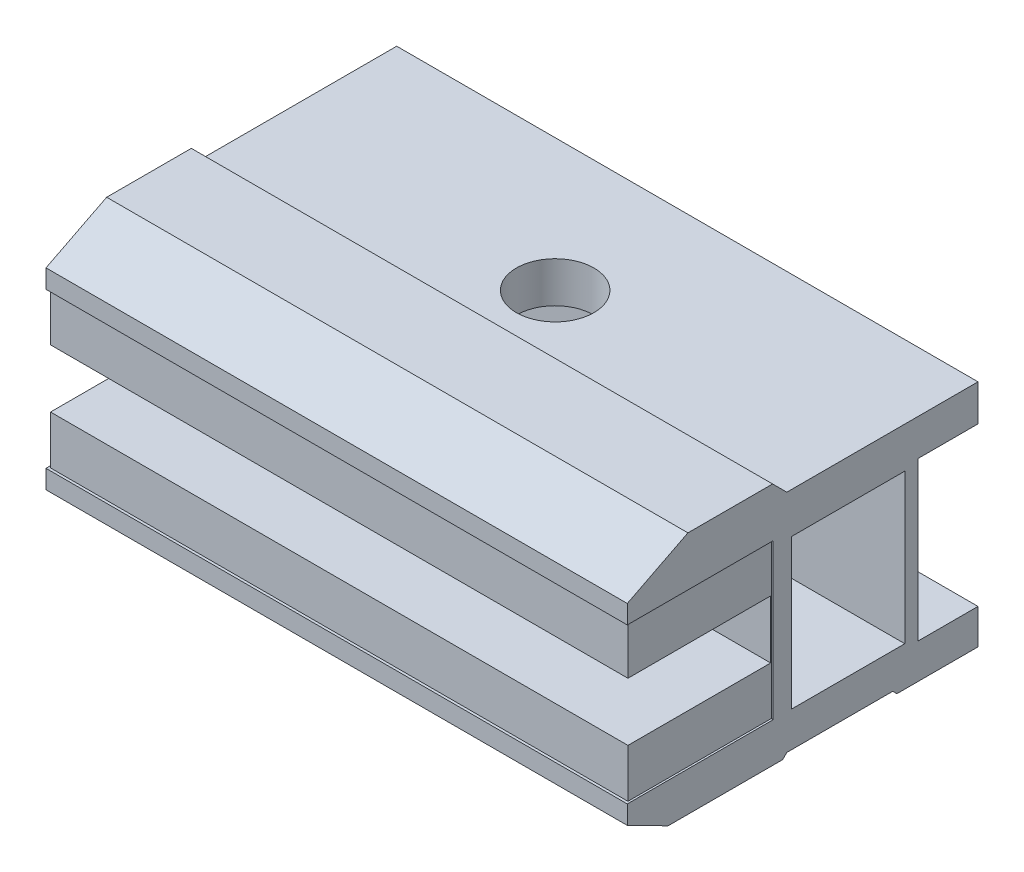
SolidWorks part; units mm, degrees
ref_plane "Plan de face" through (0, 0, 0) normal (0, 0, 1) x (1, 0, 0)
ref_plane "Plan de dessus" through (0, 0, 0) normal (0, 1, 0) x (1, 0, 0)
ref_plane "Plan de droite" through (0, 0, 0) normal (1, 0, 0) x (0, 0, -1)
sketch "Croquis1" plane through (0, 0, 0) normal (1, 0, 0) x (0, 0, -1)
  line L0 (0, 3.1818) -> (6.2594, 0)
  line L1 (6.2594, 0) -> (15, 0)
  line L2 (0, 3.1818) -> (0, 5.1025)
  line L6 (0, 5.1025) -> (0, 3.1818)
  line L7 (6.2594, 0) -> (15, 0)
  line L8 (15, 21.1025) -> (15, 5.1025)
  line L9 (30, 20.9729) -> (30, 4.6593)
  line L10 (0, 5.1025) -> (15, 5.1025)
  line L11 (15, 5.1025) -> (15, 21.1025)
  line L13 (16.9711, 5.1025) -> (28.6433, 5.1025)
  line L14 (16.9711, 5.1025) -> (16.9711, 20.5297)
  line L16 (28.6433, 5.1025) -> (28.6433, 20.5297)
  line L18 (15, 0) -> (16.4684, 1.4684)
  line L19 (16.4684, 1.4684) -> (30, 1.4684)
  line L20 (30, 1.4684) -> (36.2, 1.4684)
  line L21 (36.2, 1.4684) -> (36.2, 4.6593)
  line L22 (36.2, 4.6593) -> (30, 4.6593)
  line L23 (36.2, 20.9729) -> (30, 20.9729)
  line L24 (36.2, 24.7367) -> (36.2, 20.9729)
  line L25 (30, 24.7367) -> (36.2, 24.7367)
  line L26 (16.4684, 24.7367) -> (30, 24.7367)
  line L27 (15, 26.2051) -> (16.4684, 24.7367)
  line L28 (16.9711, 20.5297) -> (28.6433, 20.5297)
  line L29 (0, 21.1025) -> (15, 21.1025)
  line L30 (6.2594, 26.2051) -> (15, 26.2051)
  line L31 (0, 21.1025) -> (0, 23.0233)
  line L32 (0, 23.0233) -> (0, 21.1025)
  line L33 (6.2594, 26.2051) -> (15, 26.2051)
  line L34 (0, 23.0233) -> (6.2594, 26.2051)
  dimension "D1" = 36.2
  dimension "D2" = 15
  dimension "D3" = 15
  dimension "D4" = 16
extrude "Saliente-Extruir1" add sketch "Croquis1" along normal blind 60 contours L34 L31 L29 L8 L10 L2 L0 L1 L18 L19 L20 L21 L22 L9 L23 L24 L25 L26 L27 L30 L14 L28 L16 L13
sketch "Croquis2" plane through (0, 24.7367, 0) normal (0, 1, 0) x (1, 0, 0)
  line L4 (0, 36.2) -> (0, 16.4684)
  line L5 (0, 16.4684) -> (60, 16.4684)
  line L6 (60, 16.4684) -> (60, 36.2)
  line L7 (60, 36.2) -> (0, 36.2)
  line L8 (0, 16.9711) -> (0, 16.4684)
  line L10 (60, 16.4684) -> (60, 16.9711)
  circle A0 centre (30, 22.5558) radius 4
  dimension "D3" = 8
  dimension "D1" = 0
extrude "Cortar-Extruir1" cut sketch "Croquis2" against normal blind 60 contours A0
sketch "Croquis5" plane through (0, 5.1025, 0) normal (0, 1, 0) x (1, 0, 0)
  line L1 (0, 15) -> (60, 15)
  line L2 (0, 15) -> (0, 0.2676)
  line L3 (0, 0.2676) -> (60, 0.2676)
  line L4 (0, 15) -> (0, 0)
  line L5 (0, 0) -> (60, 0)
  line L6 (60, 0) -> (60, 15)
  line L7 (60, 15) -> (0, 15)
  line L8 (0, 15) -> (0, 0.2676)
  line L10 (60, 0.2676) -> (60, 15)
  line L11 (60, 15) -> (0, 15)
  line L12 (60, 15) -> (60, 0.2676)
  dimension "D1" = 0
extrude "Saliente-Extruir4" add sketch "Croquis5" along normal blind 5 contours L1 L3 L4
ref_plane "Plano1" through (0, 13.1025, 0) normal (0, 1, 0) x (1, 0, 0)
mirror "Simetría1" about plane through (0, 13.1025, 0) normal (0, 1, 0) of "Saliente-Extruir4"
sketch "Croquis6" plane through (60, 0, 0) normal (1, 0, 0) x (0, 0, -1)
  line L1 (0.2676, 21.1025) -> (15.06, 21.1025)
  line L2 (0.2676, 21.1025) -> (0.2676, 5.1025)
  line L3 (0.2676, 5.1025) -> (15.06, 5.1025)
  line L4 (15.06, 21.1025) -> (15.06, 5.1025)
extrude "Cortar-Extruir2" cut sketch "Croquis6" against normal blind 0.2
ref_plane "Plano2" through (30, 0, 0) normal (1, 0, 0) x (0, 0, -1)
mirror "Simetría2" about plane through (30, 0, 0) normal (1, 0, 0) of "Cortar-Extruir2"
sketch "Croquis7" plane through (60, 0, 0) normal (1, 0, 0) x (0, 0, -1)
  line L0 (16.0403, 1.0403) -> (4.2129, 1.0403)
  line L1 (15, 0) -> (16.4684, 1.4684) construction
  line L2 (0, 3.1818) -> (6.2594, 0) construction
  line L3 (4.2129, 1.0403) -> (2.7201, -1.8965)
  line L4 (2.7201, -1.8965) -> (18.7633, -1.8965)
  line L5 (18.7633, -1.8965) -> (16.0403, 1.0403)
extrude "Cortar-Extruir3" cut sketch "Croquis7" against normal blind 60
sketch "Croquis8" plane through (0, 0, 0) normal (-1, 0, 0) x (0, 0, 1)
  line L0 (-27.828, 1.0403) -> (-36.2, 1.0403)
  line L1 (-36.2, 1.0403) -> (-36.2, 1.4684)
  line L2 (-36.2, 1.4684) -> (-27.3999, 1.4684)
  line L3 (-16.4684, 1.4684) -> (-36.2, 1.4684) construction
  line L4 (-27.3999, 1.4684) -> (-27.828, 1.0403)
extrude "Saliente-Extruir5" add sketch "Croquis8" against normal blind 60
